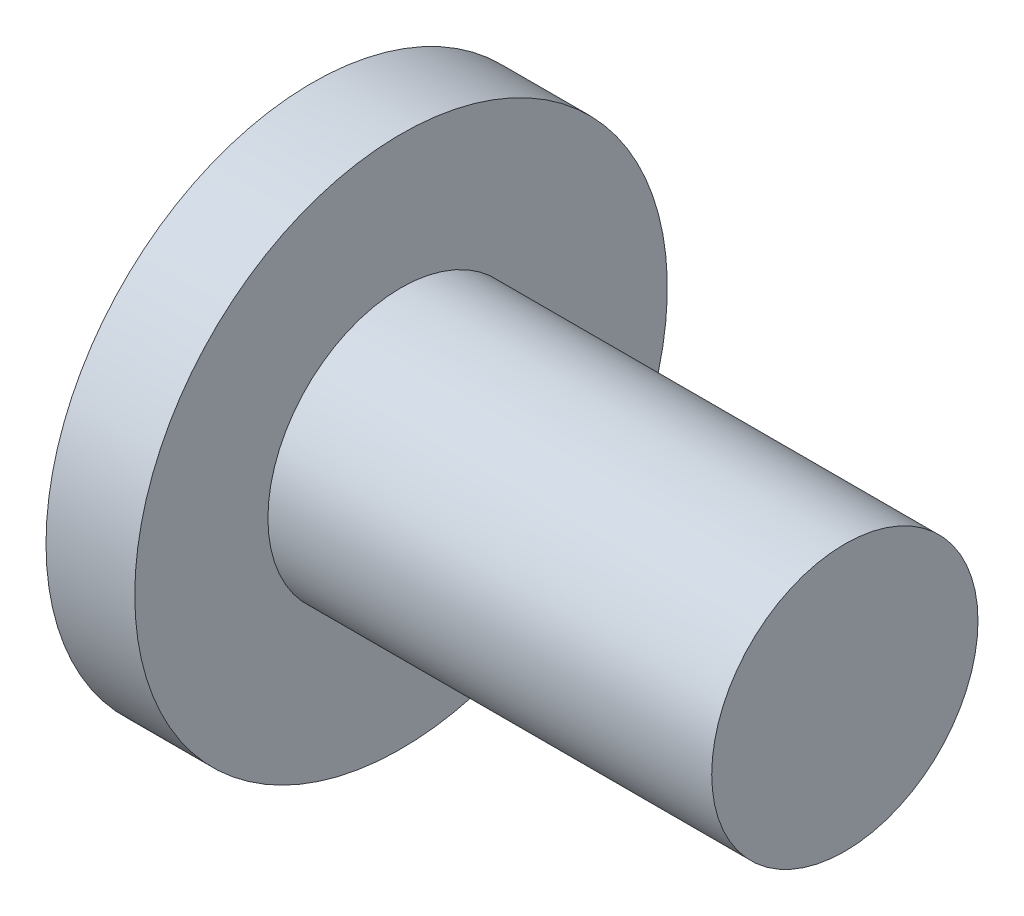
SolidWorks part; units mm, degrees
material "Alloy Steel (SS)"
ref_plane "Front Plane" through (0, 0, 0) normal (0, 0, 1) x (1, 0, 0)
ref_plane "Top Plane" through (0, 0, 0) normal (0, 1, 0) x (1, 0, 0)
ref_plane "Right Plane" through (0, 0, 0) normal (1, 0, 0) x (0, 0, -1)
sketch "Sketch1" plane through (0, 0, 0) normal (0, 0, 1) x (1, 0, 0)
  line L0 (-10.6195, 0) -> (13.6283, 0) construction
  line L1 (-6, 0) -> (-6, 6)
  line L2 (-6, 6) -> (-4, 6)
  line L3 (-4, 6) -> (-4, 3)
  line L4 (-4, 3) -> (6, 3)
  line L5 (6, 3) -> (6, 0)
  line L6 (6, 0) -> (-6, 0)
  point P9 (0, 0)
  dimension "D1" = 6
  dimension "D2" = 2
  dimension "D3" = 10
  dimension "D4" = 3
revolve "Revolve1" add sketch "Sketch1" angle 360 about L0
